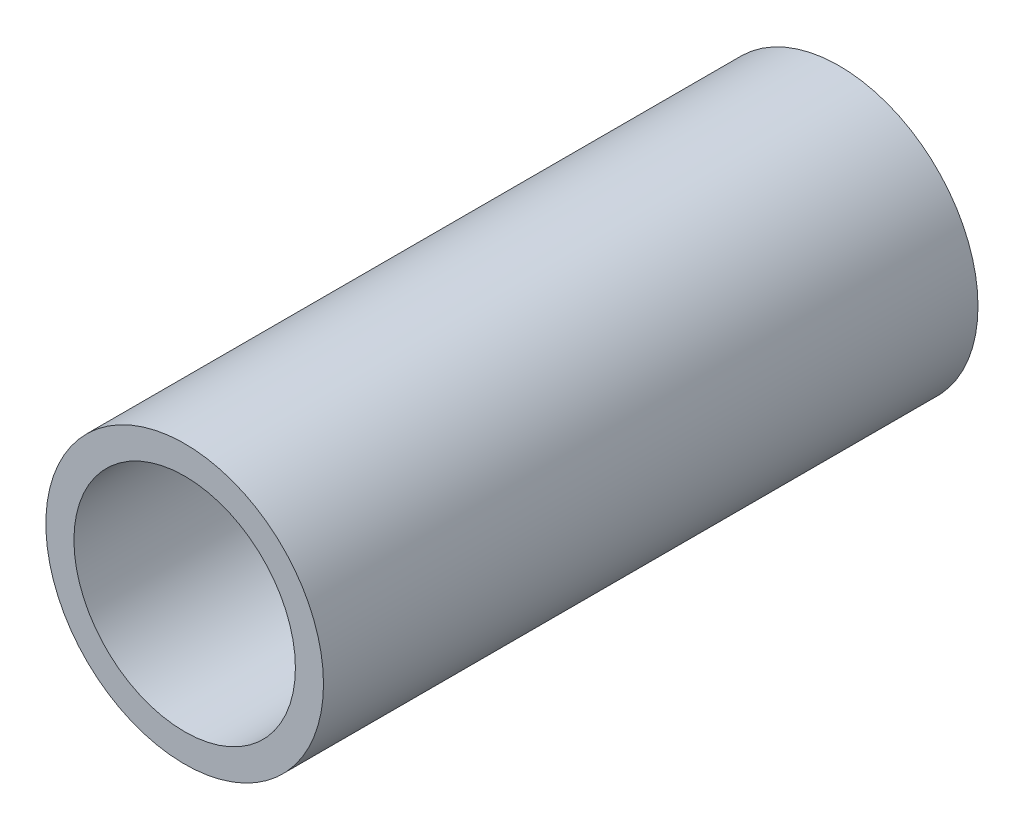
SolidWorks part; units mm, degrees
ref_plane "Front Plane" through (0, 0, 0) normal (0, 0, 1) x (1, 0, 0)
ref_plane "Top Plane" through (0, 0, 0) normal (0, 1, 0) x (1, 0, 0)
ref_plane "Right Plane" through (0, 0, 0) normal (1, 0, 0) x (0, 0, -1)
sketch "Sketch1" plane through (0, 0, 0) normal (0, 0, 1) x (1, 0, 0)
  circle A0 centre (0, 0) radius 16.7005
  dimension "Pipe OD" = 33.401
extrude "Extrude-Thin1" add sketch "Sketch1" along normal mid plane 78.74 thin thin type one direction reverse wall 3.3782
